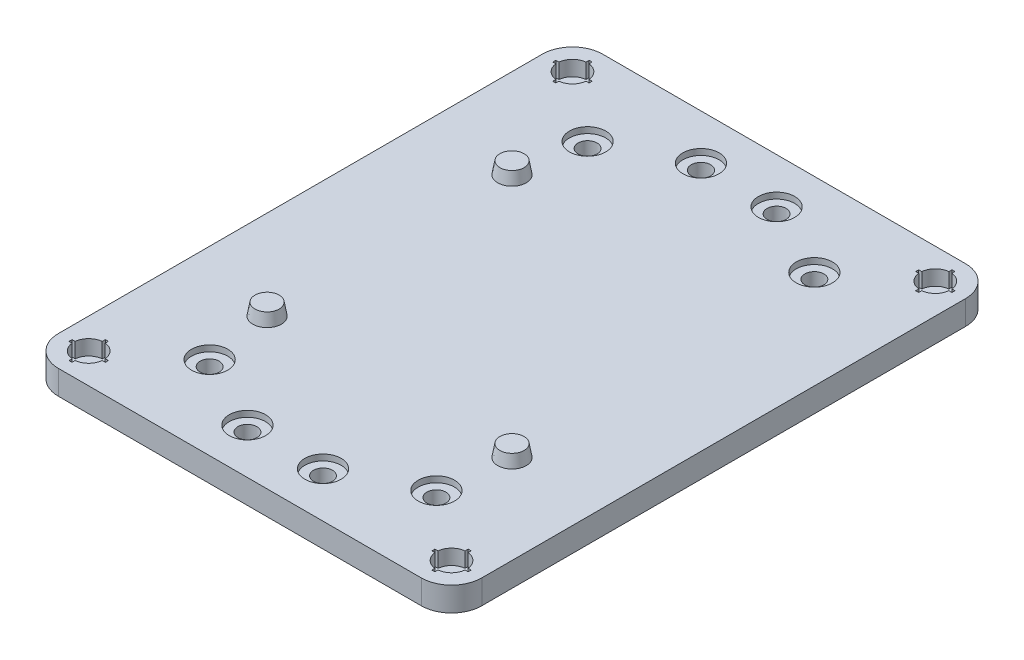
SolidWorks part; units mm, degrees
ref_plane "前视基准面" through (0, 0, 0) normal (0, 0, 1) x (1, 0, 0)
ref_plane "上视基准面" through (0, 0, 0) normal (0, 1, 0) x (1, 0, 0)
ref_plane "右视基准面" through (0, 0, 0) normal (1, 0, 0) x (0, 0, -1)
sketch "草图1" plane through (0, 0, 0) normal (0, 1, 0) x (1, 0, 0)
  line L1 (100, -100) -> (-100, -100)
  line L2 (100, -100) -> (100, 100)
  line L3 (100, 100) -> (-100, 100)
  line L4 (-100, -100) -> (-100, 100)
  line L5 (100, -100) -> (-100, 100) construction
  line L6 (100, 100) -> (-100, -100) construction
  line L7 (12.5, -75) -> (-12.5, -75) construction
  line L8 (12.5, -75) -> (12.5, 75) construction
  line L9 (12.5, 75) -> (-12.5, 75) construction
  line L10 (-12.5, -75) -> (-12.5, 75) construction
  line L11 (12.5, -75) -> (-12.5, 75) construction
  line L12 (12.5, 75) -> (-12.5, -75) construction
  line L13 (37.5, -62.5) -> (-37.5, -62.5) construction
  line L14 (37.5, -62.5) -> (37.5, 62.5) construction
  line L15 (37.5, 62.5) -> (-37.5, 62.5) construction
  line L16 (-37.5, -62.5) -> (-37.5, 62.5) construction
  line L17 (37.5, -62.5) -> (-37.5, 62.5) construction
  line L18 (37.5, 62.5) -> (-37.5, -62.5) construction
  circle A0 centre (-12.5, 75) radius 3.2
  circle A1 centre (12.5, 75) radius 3.15
  circle A2 centre (-12.5, -75) radius 3.15
  circle A3 centre (12.5, -75) radius 3.15
  circle A4 centre (-37.5, -62.5) radius 3.15
  circle A5 centre (37.5, -62.5) radius 3.15
  circle A6 centre (-37.5, 62.5) radius 3.15
  circle A7 centre (37.5, 62.5) radius 3.15
  point P0 (0, 0)
  point P6 (0, 0)
  point P11 (0, 0)
  dimension "D7" = 6.3
  dimension "D8" = 6.4
  dimension "D9" = 6.3
  dimension "D10" = 6.3
  dimension "D11" = 6.3
  dimension "D12" = 6.3
  dimension "D13" = 6.3
  dimension "D14" = 6.3
  dimension "D1" = 200
  dimension "D2" = 200
  dimension "D3" = 25
  dimension "D4" = 150
  dimension "D5" = 125
  dimension "D6" = 75
extrude "凸台-拉伸1" add sketch "草图1" along normal blind 8
sketch "草图2" plane through (0, 8, 0) normal (0, 1, 0) x (1, 0, 0)
  circle A0 centre (-37.5, 62.5) radius 6
  circle A1 centre (-12.5, 75) radius 6
  circle A2 centre (12.5, 75) radius 6
  circle A3 centre (37.5, 62.5) radius 6
  circle A4 centre (-37.5, -62.5) radius 6
  circle A5 centre (-12.5, -75) radius 6
  circle A6 centre (12.5, -75) radius 6
  circle A7 centre (37.5, -62.5) radius 6
  dimension "D1" = 12
  dimension "D2" = 12
  dimension "D3" = 12
  dimension "D4" = 12
  dimension "D5" = 12
  dimension "D6" = 12
  dimension "D7" = 12
  dimension "D8" = 12
extrude "切除-拉伸1" cut sketch "草图2" against normal blind 2
sketch "草图3" plane through (0, 8, 0) normal (0, 1, 0) x (1, 0, 0)
  line L1 (70, -90) -> (-70, -90)
  line L2 (70, -90) -> (70, 90)
  line L3 (70, 90) -> (-70, 90)
  line L4 (-70, -90) -> (-70, 90)
  line L5 (70, -90) -> (-70, 90) construction
  line L6 (70, 90) -> (-70, -90) construction
  line L7 (100, -100) -> (-100, -100)
  line L8 (100, -100) -> (100, 100)
  line L9 (100, 100) -> (-100, 100)
  line L10 (-100, -100) -> (-100, 100)
  line L11 (100, -100) -> (-100, 100) construction
  line L12 (100, 100) -> (-100, -100) construction
  point P0 (0, 0)
  point P6 (0, 0)
  dimension "D1" = 140
  dimension "D2" = 180
extrude "切除-拉伸2" cut sketch "草图3" against normal blind 10
fillet "圆角1" radius 10 1 edges at (-70, 4, -90)
fillet "圆角2" radius 10 1 edges at (70, 4, -90)
fillet "圆角3" radius 10 1 edges at (70, 4, 90)
fillet "圆角4" radius 10 1 edges at (-70, 4, 90)
sketch "草图12" plane through (0, 8, 0) normal (0, 1, 0) x (1, 0, 0)
  line L5 (-60.5, 84.9749) -> (-60.5, 86)
  line L58 (60, -80) -> (-60, -80) construction
  line L59 (60, -80) -> (60, 80) construction
  line L60 (60, 80) -> (-55, 80) construction
  line L61 (-60, -80) -> (-60, 74) construction
  line L62 (60, -80) -> (-57, 76) construction
  line L63 (60, 80) -> (-60, -80) construction
  line L64 (-59.5, 74) -> (-60.5, 74)
  line L65 (-59.5, 74) -> (-59.5, 75.0251)
  line L66 (-59.5, 86) -> (-60.5, 86)
  line L67 (-60.5, 74) -> (-60.5, 75.0251)
  line L76 (-66, 79.5) -> (-64.9749, 79.5)
  line L77 (-66, 79.5) -> (-66, 80.5)
  line L78 (-66, 80.5) -> (-64.9749, 80.5)
  line L79 (-54, 79.5) -> (-54, 80.5)
  line L95 (-55.0251, 79.5) -> (-54, 79.5)
  line L99 (-55.0251, 80.5) -> (-54, 80.5)
  line L100 (-59.5, 84.9749) -> (-59.5, 86)
  arc A8 (-55.0251, 80.5) -> (-59.5, 84.9749) centre (-60, 80) ccw
  arc A9 (-60.5, 84.9749) -> (-64.9749, 80.5) centre (-60, 80) ccw
  arc A10 (-64.9749, 79.5) -> (-60.5, 75.0251) centre (-60, 80) ccw
  arc A11 (-59.5, 75.0251) -> (-55.0251, 79.5) centre (-60, 80) ccw
  point P0 (0, 0)
  point P1 (0, 0)
  dimension "D3" = 1
  dimension "D1" = 120
  dimension "D2" = 160
  dimension "D4" = 1
  dimension "D5" = 12
  dimension "D6" = 12
extrude "切除-拉伸5" cut sketch "草图12" against normal blind 5
mirror "镜向7" about plane through (0, 0, 0) normal (0, 0, 1) of "切除-拉伸5" second plane through (0, 0, 0) second plane normal (1, 0, 0)
sketch "草图15" plane through (0, 8, 0) normal (0, 1, 0) x (1, 0, 0)
  line L4 (40.5, -40.5) -> (-40.5, -40.5) construction
  line L5 (40.5, -40.5) -> (40.5, 40.5) construction
  line L6 (40.5, 40.5) -> (-40.5, 40.5) construction
  line L7 (-40.5, -40.5) -> (-40.5, 40.5) construction
  line L8 (40.5, -40.5) -> (-40.5, 40.5) construction
  line L9 (40.5, 40.5) -> (-40.5, -40.5) construction
  circle A3 centre (-40.5, -40.5) radius 4
  point P0 (0, 0)
  dimension "D1" = 81
  dimension "D2" = 81
extrude "凸台-拉伸2" add sketch "草图15" along normal blind 4
draft "拔模3" type of draft neutral plane draft angle 10 faces to draft 1 face at (-40.5, 12, 44.5) neutral plane through (-40.5, 12, 40.5) neutral plane normal (0, 1, 0) parameters "D1"=10
mirror "镜向13" about plane through (0, 0, 0) normal (0, 0, 1) of "凸台-拉伸2", "拔模3"
mirror "镜向14" about plane through (0, 0, 0) normal (1, 0, 0) of "拔模3", "凸台-拉伸2"
sketch "草图16" plane through (0, 8, 0) normal (0, 1, 0) x (1, 0, 0)
  circle A0 centre (-60, 80) radius 1.2
extrude "切除-拉伸6" cut sketch "草图16" against normal through all
mirror "镜向15" about plane through (0, 0, 0) normal (0, 0, 1) of "切除-拉伸6" second plane through (0, 0, 0) second plane normal (1, 0, 0)
